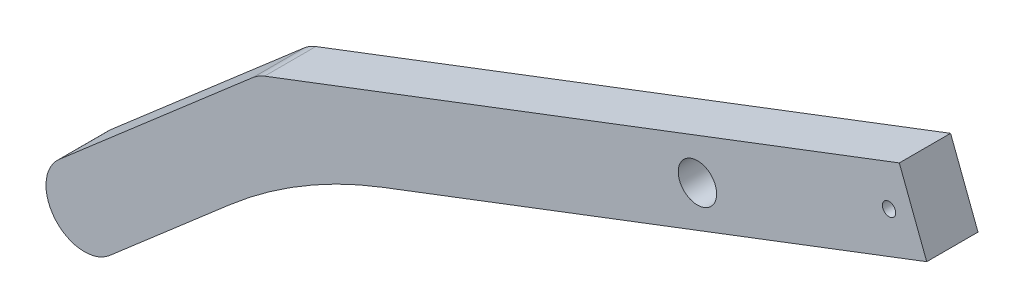
SolidWorks part; units mm, degrees
ref_plane "前视基准面" through (0, 0, 0) normal (0, 0, 1) x (1, 0, 0)
ref_plane "上视基准面" through (0, 0, 0) normal (0, 1, 0) x (1, 0, 0)
ref_plane "右视基准面" through (0, 0, 0) normal (1, 0, 0) x (0, 0, -1)
other "Configuration Table"
sketch "草图1" plane through (0, 0, 0) normal (0, 0, 1) x (1, 0, 0)
  line L0 (-90.1826, -3.6872) -> (-165.784, -69.1428)
  line L3 (-146.1474, -91.8232) -> (-99.2067, -51.182)
  line L4 (-39.5974, -15.5264) -> (172.5707, 65.4331)
  line L5 (172.5707, 65.4331) -> (161.8754, 93.4618)
  line L6 (161.8754, 93.4618) -> (-85.7119, -1.013)
  circle A5 centre (157.8801, 75.8823) radius 2.6
  arc A6 (-85.7119, -1.013) -> (-90.1826, -3.6872) centre (-80.3643, -15.0274) ccw
  arc A7 (-165.784, -69.1428) -> (-146.1474, -91.8232) centre (-155.9657, -80.483) ccw
  arc A8 (-39.5974, -15.5264) -> (-99.2067, -51.182) centre (31.7044, -202.3848) ccw
  circle A9 centre (83.1368, 47.3616) radius 7.5
extrude "凸台-拉伸1" add sketch "草图1" along normal blind 20
